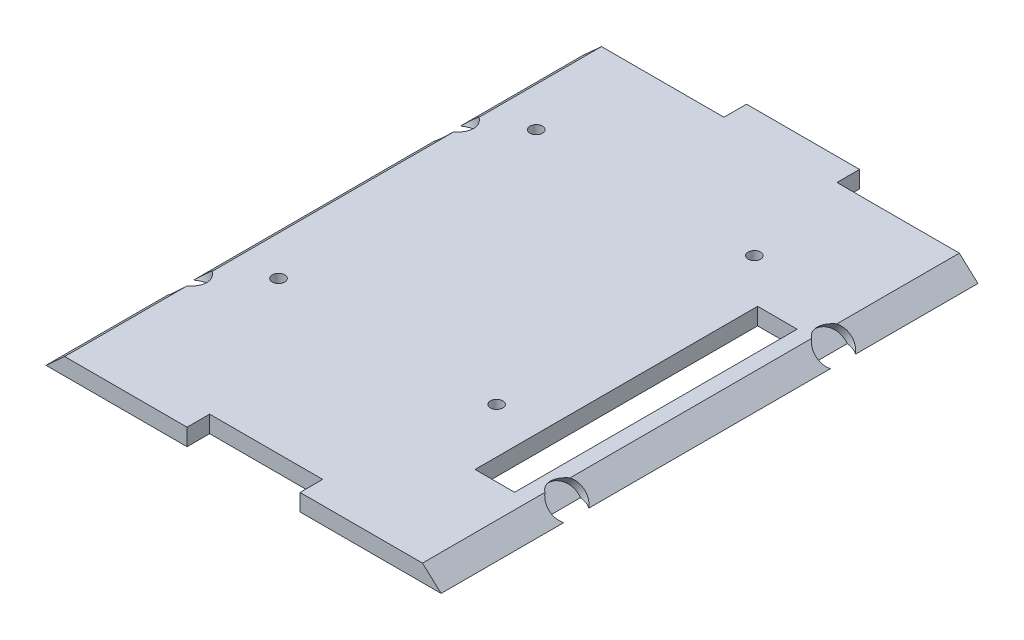
SolidWorks part; units mm, degrees
ref_plane "Front Plane" through (0, 0, 0) normal (0, 0, 1) x (1, 0, 0)
ref_plane "Top Plane" through (0, 0, 0) normal (0, 1, 0) x (1, 0, 0)
ref_plane "Right Plane" through (0, 0, 0) normal (1, 0, 0) x (0, 0, -1)
sketch "Sketch1" plane through (0, 0, 0) normal (0, 0, 1) x (1, 0, 0)
  line L0 (0, 0) -> (0, 44.45) construction
  line L1 (-40.2039, 5.9378) -> (40.2039, 5.9378)
  line L2 (-44.399, 2.1278) -> (44.399, 2.1278)
  line L3 (-40.2039, 5.9378) -> (-44.399, 2.1278)
  line L4 (40.2039, 5.9378) -> (44.399, 2.1278)
  arc A0 (44.399, 2.1278) -> (-44.399, 2.1278) centre (0, 0) ccw construction
  arc A1 (40.2039, 5.9378) -> (-40.2039, 5.9378) centre (0, 0) ccw construction
  dimension "D1" = 88.9
  dimension "D2" = 3.81
  dimension "D3" = 3.81
extrude "Boss-Extrude1" add sketch "Sketch1" along normal blind 120.65
sketch "Sketch2" plane through (0, 2.1278, 0) normal (0, -1, 0) x (1, 0, 0)
  line L0 (0, 120.65) -> (0, 0) construction
  line L1 (-34.417, 108.712) -> (20.701, 108.712) construction
  line L2 (-34.417, 108.712) -> (-34.417, 23.622) construction
  line L3 (-34.417, 23.622) -> (20.701, 23.622) construction
  line L4 (20.701, 108.712) -> (20.701, 23.622) construction
  line L5 (-44.399, 120.65) -> (44.399, 120.65) construction
  line L6 (-44.399, 0) -> (44.399, 0) construction
  line L7 (-34.417, 66.167) -> (20.701, 66.167) construction
  line L8 (-6.858, 108.712) -> (-6.858, 23.622) construction
  line L10 (40.2039, 0) -> (-40.2039, 0) construction
  circle A0 centre (-31.369, 81.43) radius 1.397
  circle A1 centre (17.653, 23.518) radius 1.397
  circle A2 centre (-31.369, 23.518) radius 1.397
  circle A3 centre (17.653, 81.43) radius 1.397
  point P10 (-6.858, 108.712)
  dimension "D4" = 2.794
  dimension "D7" = 2.794
  dimension "D8" = 57.912
  dimension "D5" = 49.022
  dimension "D1" = 6.858
  dimension "D2" = 85.09
  dimension "D3" = 23.622
  dimension "D6" = 55.118
extrude "Cut-Extrude1" cut sketch "Sketch2" against normal through all
sketch "Sketch3" plane through (0, 2.1278, 0) normal (0, -1, 0) x (1, 0, 0)
  line L0 (0, 120.65) -> (0, 0) construction
  line L1 (-44.399, 120.65) -> (44.399, 120.65) construction
  line L2 (-44.399, 0) -> (44.399, 0) construction
  line L3 (0, 60.325) -> (44.399, 60.325) construction
  line L4 (-12.7, 120.65) -> (12.7, 120.65)
  line L5 (-12.7, 120.65) -> (-12.7, 115.57)
  line L6 (-12.7, 115.57) -> (12.7, 115.57)
  line L7 (12.7, 120.65) -> (12.7, 115.57)
  line L8 (44.399, 120.65) -> (44.399, 0) construction
  line L9 (0, 60.325) -> (-44.399, 60.325) construction
  line L10 (-44.399, 120.65) -> (-44.399, 0) construction
  line L11 (12.7, 0) -> (12.7, 5.08)
  line L12 (-12.7, 5.08) -> (12.7, 5.08)
  line L13 (-12.7, 0) -> (12.7, 0)
  line L14 (-12.7, 0) -> (-12.7, 5.08)
  point P10 (12.7, 118.11)
  dimension "D1" = 25.4
  dimension "D2" = 12.7
  dimension "D3" = 5.08
extrude "Cut-Extrude2" cut sketch "Sketch3" against normal through all
sketch "Sketch5" plane through (0, 2.1278, 0) normal (0, -1, 0) x (1, 0, 0)
  line L0 (12.7, 0) -> (12.7, 5.08) construction
  line L1 (12.7, 5.08) -> (-12.7, 5.08)
  line L2 (12.7, 5.08) -> (12.7, -5.08)
  line L3 (12.7, -5.08) -> (-12.7, -5.08)
  line L4 (-12.7, 5.08) -> (-12.7, -5.08)
  line L5 (12.7, 5.08) -> (-12.7, 5.08) construction
  dimension "D1" = 0
  dimension "D2" = 25.4
  dimension "D3" = 10.16
extrude "Boss-Extrude3" add sketch "Sketch5" against normal blind 3.81
sketch "Sketch6" plane through (0, 2.1278, 0) normal (0, -1, 0) x (1, 0, 0)
  line L0 (12.7, 120.65) -> (44.399, 120.65) construction
  line L1 (27.889, 96.52) -> (36.779, 96.52)
  line L2 (27.889, 96.52) -> (27.889, 33.02)
  line L3 (27.889, 33.02) -> (36.779, 33.02)
  line L4 (36.779, 96.52) -> (36.779, 33.02)
  line L5 (44.399, 120.65) -> (44.399, 0) construction
  dimension "D1" = 24.13
  dimension "D2" = 7.62
  dimension "D3" = 63.5
  dimension "D4" = 8.89
extrude "Cut-Extrude3" cut sketch "Sketch6" against normal through all
sketch "Sketch7" plane through (21.1272, 23.263, 0) normal (0.6723, 0.7403, 0) x (0.7403, -0.6723, 0)
  line L0 (28.6033, -120.65) -> (28.6033, 0) construction
  line L1 (31.4368, -120.65) -> (25.7698, -120.65) construction
  line L2 (25.7698, -60.325) -> (31.987, -60.325) construction
  line L3 (25.7698, -120.65) -> (25.7698, 0) construction
  circle A0 centre (28.6033, -90.297) radius 4
  circle A1 centre (28.6033, -30.353) radius 4
  dimension "D1" = 8
  dimension "D2" = 29.972
  dimension "D3" = 120.65
extrude "Cut-Extrude4" cut sketch "Sketch7" against normal blind 2
sketch "Sketch8" plane through (-21.1272, 23.263, 0) normal (-0.6723, 0.7403, 0) x (0.7403, 0.6723, 0)
  line L0 (-28.6033, 0) -> (-28.6033, -120.65) construction
  line L1 (-25.7698, 0) -> (-31.4368, 0) construction
  line L2 (-25.7698, -60.325) -> (-31.4368, -60.325) construction
  line L3 (-25.7698, -120.65) -> (-25.7698, 0) construction
  line L4 (-31.4368, -120.65) -> (-31.4368, 0) construction
  circle A0 centre (-28.6033, -30.353) radius 4
  circle A1 centre (-28.6033, -90.297) radius 4
  dimension "D1" = 8
  dimension "D2" = 29.972
  dimension "D3" = 120.65
extrude "Cut-Extrude5" cut sketch "Sketch8" against normal blind 2
